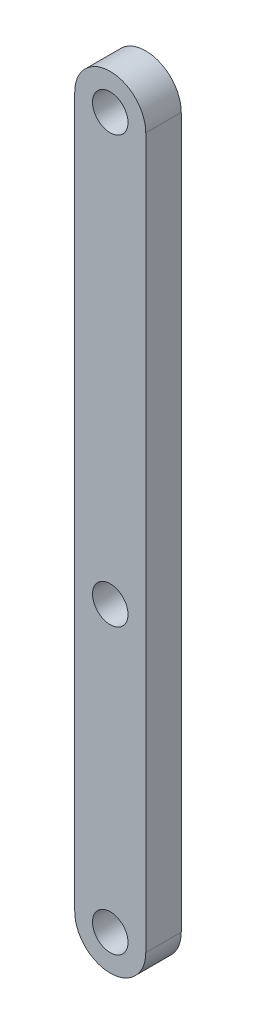
SolidWorks part; units mm, degrees
ref_plane "Front Plane" through (0, 0, 0) normal (0, 0, 1) x (1, 0, 0)
ref_plane "Top Plane" through (0, 0, 0) normal (0, 1, 0) x (1, 0, 0)
ref_plane "Right Plane" through (0, 0, 0) normal (1, 0, 0) x (0, 0, -1)
sketch "Sketch1" plane through (0, 0, 0) normal (0, 0, 1) x (1, 0, 0)
  line L0 (0, 0) -> (0, -40) construction
  line L1 (2, 0) -> (2, -40)
  line L2 (-2, -40) -> (-2, 0)
  circle A0 centre (0, 0) radius 1
  arc A1 (2, 0) -> (-2, 0) centre (0, 0) ccw
  circle A2 centre (0, -40) radius 1
  circle A3 centre (0, -24) radius 1
  arc A4 (-2, -40) -> (2, -40) centre (0, -40) ccw
  point P13 (2, -40)
  point P14 (-2, -40)
  point P15 (-2, 0)
  dimension "D1" = 2
  dimension "D2" = 4
  dimension "D4" = 2
  dimension "D6" = 2
  dimension "D7" = 4
  dimension "D3" = 40
  dimension "D5" = 24
extrude "Boss-Extrude1" add sketch "Sketch1" along normal blind 2
